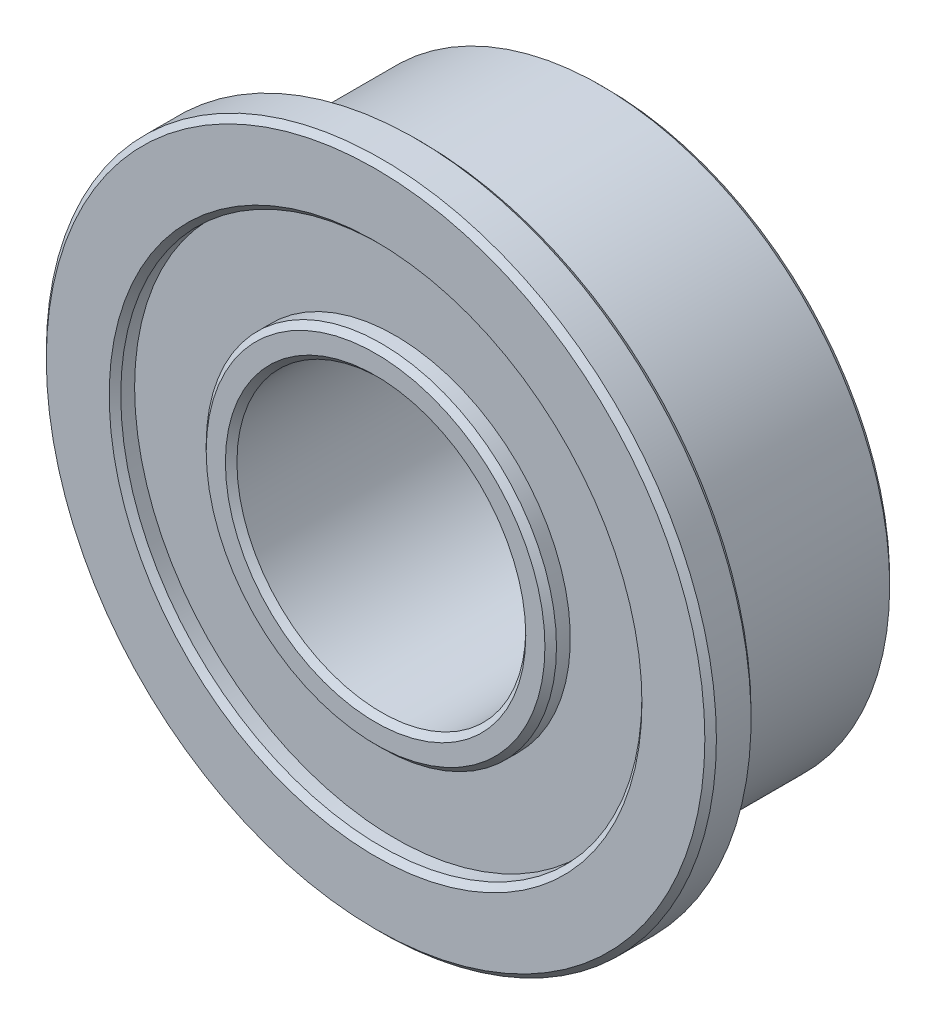
SolidWorks part; units mm, degrees
ref_plane "Front Plane" through (0, 0, 0) normal (0, 0, 1) x (1, 0, 0)
ref_plane "Top Plane" through (0, 0, 0) normal (0, 1, 0) x (1, 0, 0)
ref_plane "Right Plane" through (0, 0, 0) normal (1, 0, 0) x (0, 0, -1)
ref_axis "Axis1" through (0, 0, -19.0783) along (0, 0, 1)
sketch "Sketch1" plane through (0, 0, 0) normal (1, 0, 0) x (0, 0, -1)
  line L0 (19.0783, 0) -> (-24.5011, 0) construction
  line L1 (-1.2, 5) -> (2, 5)
  line L2 (-2, 5) -> (-2, 2.5) construction
  line L3 (-2, 2.5) -> (2, 2.5)
  line L4 (2, 5) -> (2, 4.511)
  line L5 (-2, 5) -> (2, 2.5) construction
  line L6 (-2, 2.5) -> (2, 5) construction
  line L7 (0, 3.75) -> (0, 0) construction
  line L8 (2, 3.0318) -> (2, 2.5)
  line L9 (2, 4.511) -> (1.6603, 4.511)
  line L10 (-2, 3.0318) -> (-2, 2.5)
  line L11 (2, 3.0318) -> (1.6603, 3.0318)
  line L12 (1.6603, 4.511) -> (1.6603, 3.0318)
  line L13 (-2, 3.0318) -> (-1.6603, 3.0318)
  line L14 (-1.6603, 4.511) -> (-1.6603, 3.0318)
  line L15 (-2, 4.511) -> (-1.6603, 4.511)
  line L16 (-2, 5) -> (-2, 4.511) construction
  line L17 (-1.2, 5) -> (-1.2, 5.8)
  line L18 (-1.2, 5.8) -> (-2, 5.8)
  line L19 (-2, 5.8) -> (-2, 4.511)
  point P0 (0, 3.75)
  dimension "D1" = 5
  dimension "D2" = 4
  dimension "D3" = 2.5
  dimension "D4" = 0.8
  dimension "D5" = 5.8
revolve "Revolve1" add sketch "Sketch1" angle 360 about axis through (0, 0, -19.0783) along (0, 0, 1)
chamfer "Chamfer1" distance 0.1 angle 45 9 edges at (-2.5, 0, -2) (-2.5, 0, 2) (-5, 0, -2) (-4.511, 0, -2) (-3.0318, 0, -2) (-3.0318, 0, 2) (-4.511, 0, 2) (-5.8, 0, 1.2) (-5.8, 0, 2)
